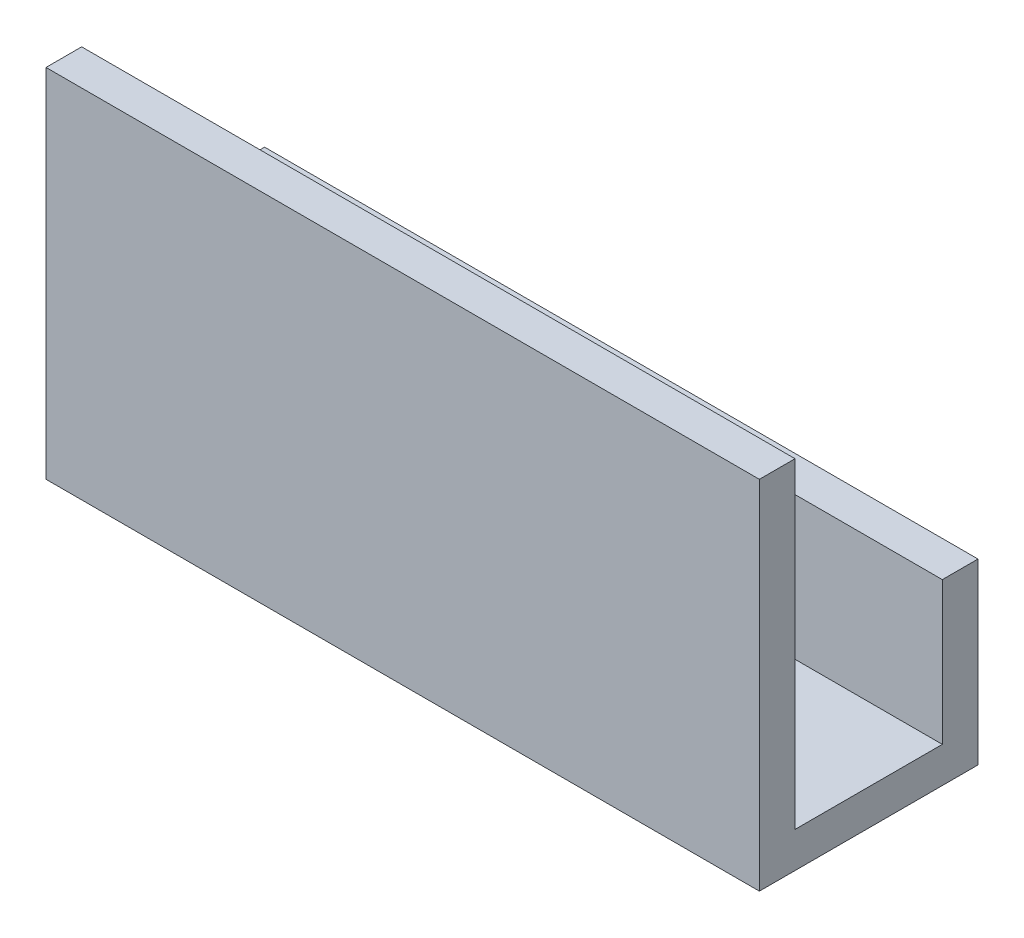
SolidWorks part; units mm, degrees
ref_plane "Front Plane" through (0, 0, 0) normal (0, 0, 1) x (1, 0, 0)
ref_plane "Top Plane" through (0, 0, 0) normal (0, 1, 0) x (1, 0, 0)
ref_plane "Right Plane" through (0, 0, 0) normal (1, 0, 0) x (0, 0, -1)
sketch "Sketch1" plane through (0, 0, 0) normal (1, 0, 0) x (0, 0, -1)
  line L0 (7.7838, 0) -> (-7.7838, 0)
  line L1 (-7.7838, 0) -> (-7.7838, 25.4)
  line L2 (7.7838, 0) -> (7.7838, 12.7)
  line L3 (5.2438, 2.54) -> (5.2438, 12.7)
  line L4 (5.2438, 2.54) -> (-5.2438, 2.54)
  line L5 (-5.2438, 2.54) -> (-5.2438, 25.4)
  line L6 (-7.7838, 25.4) -> (-5.2438, 25.4)
  line L7 (5.2438, 12.7) -> (7.7838, 12.7)
  point P3 (0, 0)
  dimension "D1" = 15.5677
  dimension "D2" = 12.7
  dimension "D3" = 25.4
  dimension "D4" = 2.54
extrude "Boss-Extrude1" add sketch "Sketch1" along normal mid plane 50.8
